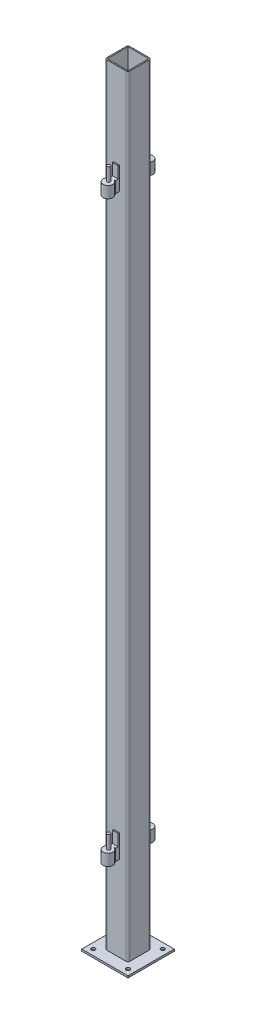
SolidWorks part; units mm, degrees
ref_plane "前视" through (0, 0, 0) normal (0, 0, 1) x (1, 0, 0)
ref_plane "上视" through (0, 0, 0) normal (0, 1, 0) x (1, 0, 0)
ref_plane "右视" through (0, 0, 0) normal (1, 0, 0) x (0, 0, -1)
sketch "草图1" plane through (0, 0, 0) normal (0, 1, 0) x (1, 0, 0)
  line L0 (0, 0) -> (0, 57.1093) construction
  line L1 (-60, 60) -> (60, 60)
  line L2 (-60, 60) -> (-60, -60)
  line L3 (-60, -60) -> (60, -60)
  line L4 (60, 60) -> (60, -60)
  line L5 (0, 0) -> (82.0444, 0) construction
  dimension "D1" = 120
  dimension "D2" = 120
extrude "凸台-拉伸1" add sketch "草图1" along normal blind 5
sketch "草图2" plane through (0, 5, 0) normal (0, 1, 0) x (1, 0, 0)
  line L13 (-30, 60) -> (-30, -60)
  line L14 (-30, 30) -> (-30, -30)
  line L20 (27, 27) -> (-27, 27)
  line L21 (-27, 27) -> (-27, -27)
  line L22 (-27, -27) -> (27, -27)
  line L23 (-60, -30) -> (30, -30)
  line L24 (30, -30) -> (30, 30)
  line L25 (30, 30) -> (-60, 30)
  line L26 (-30, -30) -> (30, -30)
  line L27 (30, -30) -> (30, 30)
  line L28 (30, 30) -> (-30, 30)
  line L29 (27, -27) -> (27, 27)
  dimension "D1" = 30
  dimension "D2" = 30
  dimension "D3" = 3
extrude "凸台-拉伸2" add sketch "草图2" along normal blind 2000
fillet "圆角1" radius 5 4 edges at (-30, 1005, 30) (30, 1005, 30) (-30, 1005, -30) (30, 1005, -30)
sketch "草图3" plane through (0, 5, 0) normal (0, 1, 0) x (1, 0, 0)
  circle A0 centre (-45, 45) radius 5
  circle A1 centre (45, 45) radius 5
  circle A2 centre (-45, -45) radius 5
  circle A3 centre (45, -45) radius 5
  dimension "D1" = 10
  dimension "D2" = 90
  dimension "D3" = 45
  dimension "D4" = 90
  dimension "D5" = 45
extrude "切除-拉伸1" cut sketch "草图3" against normal blind 2000
ref_plane "基准面1" through (0, 0, 0) normal (1, 0, 0) x (0, 0, -1)
sketch "草图6" plane through (0, 0, 0) normal (1, 0, 0) x (0, 0, -1)
  line L0 (30, 2005) -> (30, 5) construction
  line L1 (30, 1785) -> (30, 1725)
  line L2 (30, 1785) -> (33, 1785)
  line L3 (33, 1785) -> (33, 1755)
  line L4 (33, 1755) -> (40, 1755)
  line L5 (40, 1755) -> (40, 1725)
  line L6 (40, 1725) -> (30, 1725)
  line L7 (-25, 2005) -> (25, 2005) construction
  dimension "D1" = 30
  dimension "D2" = 60
  dimension "D3" = 10
  dimension "D4" = 3
  dimension "D5" = 220
extrude "凸台-拉伸5" add sketch "草图6" along normal mid plane 15
pattern_linear "阵列(线性)1" count 2 spacing 1500 along (0, -1, 0) of "凸台-拉伸5"
sketch "草图7" plane through (0, 1755, 0) normal (0, 1, 0) x (1, 0, 0)
  line L0 (7.5, 40) -> (-7.5, 40) construction
  circle A0 centre (0, 52) radius 12.5
  dimension "D1" = 25
  dimension "D2" = 12
extrude "凸台-拉伸6" add sketch "草图7" against normal blind 30
sketch "草图8" plane through (0, 1755, 0) normal (0, 1, 0) x (1, 0, 0)
  circle A0 centre (0, 50) radius 4
  arc A1 (3.5, 40) -> (-3.5, 40) centre (0, 52) ccw construction
  dimension "D2" = 8
  dimension "D1" = 2
extrude "凸台-拉伸7" add sketch "草图8" along normal blind 35
pattern_linear "阵列(线性)2" count 2 spacing 1500 along (0, -1, 0) of "凸台-拉伸7", "凸台-拉伸6"
ref_plane "基准面2" through (0, 0, 0) normal (0, 0, -1) x (-1, 0, 0)
mirror "镜向1" about plane through (0, 0, 0) normal (0, 0, -1) of "阵列(线性)1", "凸台-拉伸5", "阵列(线性)2", "凸台-拉伸7", "凸台-拉伸6"
